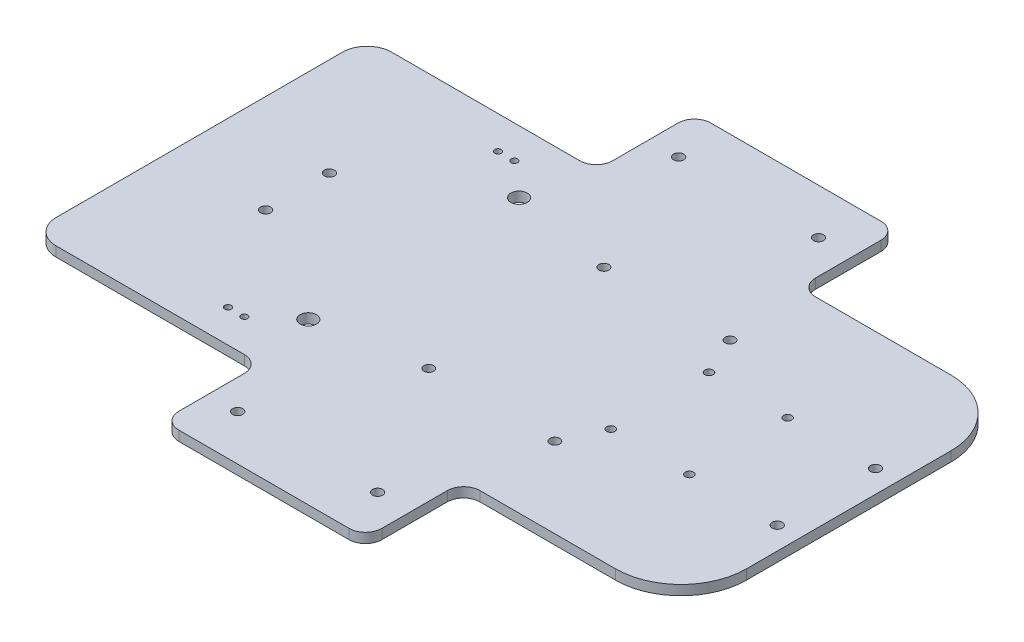
SolidWorks part; units mm, degrees
ref_plane "前视基准面" through (0, 0, 0) normal (0, 0, 1) x (1, 0, 0)
ref_plane "上视基准面" through (0, 0, 0) normal (0, 1, 0) x (1, 0, 0)
ref_plane "右视基准面" through (0, 0, 0) normal (1, 0, 0) x (0, 0, -1)
sketch "草图1" plane through (0, 0, 0) normal (0, 1, 0) x (1, 0, 0)
  line L8 (132, -5) -> (132, -25)
  line L9 (127, -30) -> (75, -30)
  line L10 (70, -25) -> (70, -5)
  line L12 (0, 51.25) -> (198.3957, 51.25) construction
  line L29 (198.3957, 82.5) -> (198.3957, 20)
  line L40 (0, 95) -> (0, 7.5)
  line L42 (137, 102.5) -> (178.3957, 102.5)
  line L43 (137, 0) -> (178.3957, 0)
  line L45 (7.5, 0) -> (65, 0)
  line L46 (127, 132.5) -> (75, 132.5)
  line L47 (70, 127.5) -> (70, 107.5)
  line L48 (7.5, 102.5) -> (65, 102.5)
  line L49 (132, 107.5) -> (132, 127.5)
  circle A0 centre (96.8555, 24.5) radius 1.5
  circle A1 centre (135.3555, 24.5) radius 1.5
  circle A5 centre (65.4779, 19.0594) radius 2.5
  circle A11 centre (30, 41.5) radius 1.55
  circle A16 centre (140.7051, 36.25) radius 1.25
  circle A17 centre (164.7051, 36.25) radius 1.25
  circle A18 centre (79.0742, -16.0984) radius 1.55
  circle A19 centre (121.8034, -16.0984) radius 1.55
  circle A22 centre (50, 10) radius 1
  arc A45 (0, 7.5) -> (7.5, 0) centre (7.5, 7.5) ccw
  arc A47 (70, -5) -> (65, 0) centre (65, -5) ccw
  arc A49 (70, -25) -> (75, -30) centre (75, -25) ccw
  arc A51 (127, -30) -> (132, -25) centre (127, -25) ccw
  arc A53 (137, 0) -> (132, -5) centre (137, -5) ccw
  circle A54 centre (164.7051, 66.25) radius 1.25
  circle A55 centre (140.7051, 66.25) radius 1.25
  circle A56 centre (135.3555, 78) radius 1.5
  circle A58 centre (96.8555, 78) radius 1.5
  circle A59 centre (65.4779, 83.4406) radius 2.5
  circle A61 centre (50, 92.5) radius 1
  circle A62 centre (30, 61) radius 1.55
  arc A63 (137, 102.5) -> (132, 107.5) centre (137, 107.5) cw
  arc A64 (127, 132.5) -> (132, 127.5) centre (127, 127.5) cw
  arc A65 (70, 127.5) -> (75, 132.5) centre (75, 127.5) cw
  arc A66 (70, 107.5) -> (65, 102.5) centre (65, 107.5) cw
  arc A67 (0, 95) -> (7.5, 102.5) centre (7.5, 95) cw
  circle A68 centre (55, 10) radius 1
  circle A69 centre (55, 92.5) radius 1
  circle A70 centre (121.8034, 118.5984) radius 1.55
  circle A71 centre (79.0742, 118.5984) radius 1.55
  circle A72 centre (191.5457, 36.25) radius 1.55
  arc A74 (178.3957, 0) -> (198.3957, 20) centre (178.3957, 20) ccw
  arc A75 (178.3957, 102.5) -> (198.3957, 82.5) centre (178.3957, 82.5) cw
  circle A76 centre (191.5457, 66.25) radius 1.55
  dimension "D18" = 10
  dimension "D11" = 26.75
  dimension "D13" = 15
  dimension "D14" = 67.3484
  dimension "D10" = 38.5
  dimension "D9" = 50
  dimension "D12" = 24
  dimension "D15" = 42.7292
  dimension "D16" = 32.1906
  dimension "D19" = 5
  dimension "D20" = 6.85
  dimension "D17" = 5
  dimension "D3" = 5
  dimension "D1" = 30
  dimension "D2" = 7.5
  dimension "D4" = 9.75
  dimension "D5" = 30
  dimension "D6" = 5
  dimension "D7" = 57.5
  dimension "D8" = 5
extrude "凸台-拉伸1" add sketch "草图1" along normal mid plane 3
